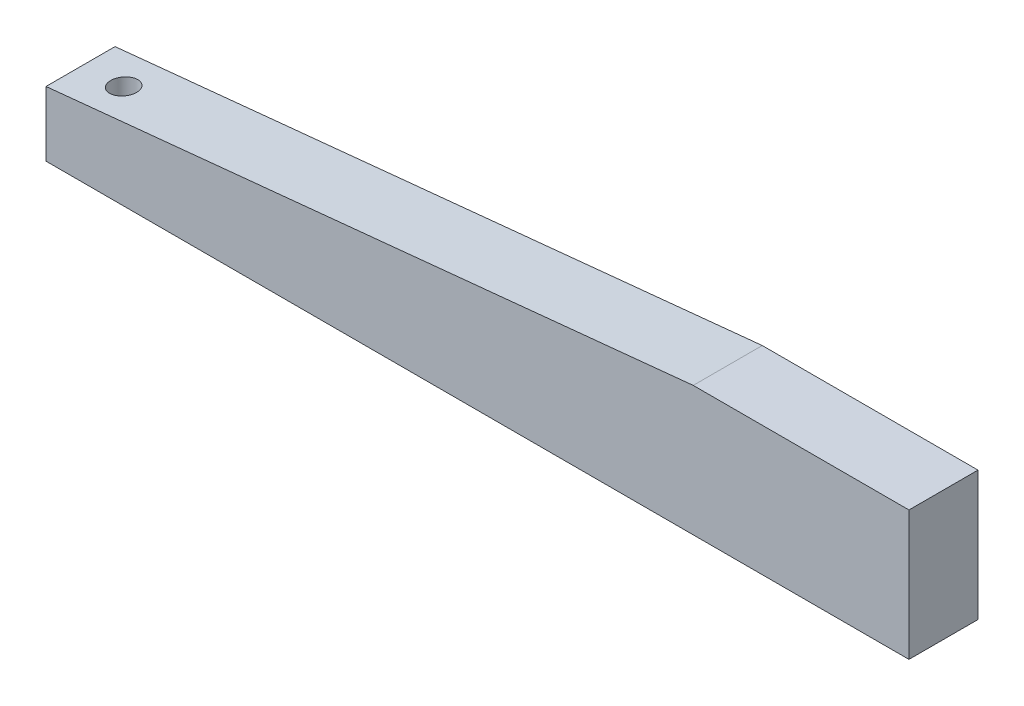
SolidWorks part; units mm, degrees
ref_plane "Plan de face" through (0, 0, 0) normal (0, 0, 1) x (1, 0, 0)
ref_plane "Plan de dessus" through (0, 0, 0) normal (0, 1, 0) x (1, 0, 0)
ref_plane "Plan de droite" through (0, 0, 0) normal (1, 0, 0) x (0, 0, -1)
sketch "Esquisse1" plane through (0, 0, 0) normal (0, 0, 1) x (1, 0, 0)
  line L0 (0, 0) -> (200, 0)
  line L1 (200, 0) -> (200, 30)
  line L2 (200, 30) -> (150, 30)
  line L3 (150, 30) -> (0, 15)
  line L4 (0, 15) -> (0, 0)
  dimension "D1" = 200
  dimension "D2" = 50
  dimension "D3" = 15
  dimension "D4" = 30
extrude "Boss.-Extru.1" add sketch "Esquisse1" along normal blind 16
sketch "Esquisse2" plane through (0, 0, 0) normal (0, -1, 0) x (1, 0, 0)
  line L0 (10, 8) -> (0, 8) construction
  line L1 (0, 16) -> (0, 0) construction
  circle A0 centre (10, 8) radius 3
  dimension "D1" = 6
  dimension "D2" = 10
extrude "Enlèv. mat.-Extru.1" cut sketch "Esquisse2" against normal through all both and the other way through all
